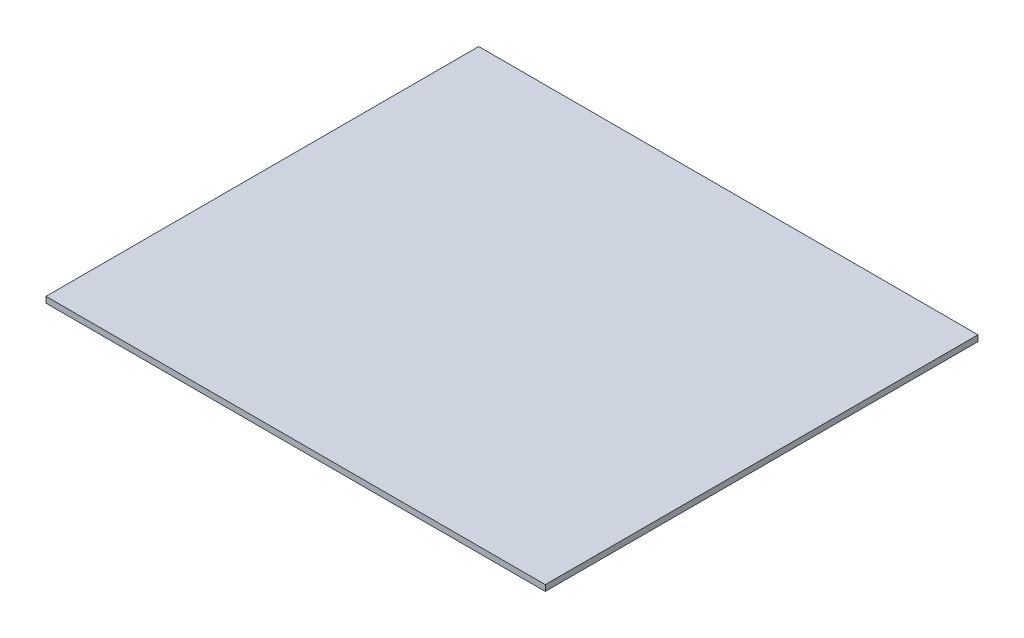
SolidWorks part; units mm, degrees
ref_plane "Front" through (0, 0, 0) normal (0, 0, 1) x (1, 0, 0)
ref_plane "Top" through (0, 0, 0) normal (0, 1, 0) x (1, 0, 0)
ref_plane "Right" through (0, 0, 0) normal (1, 0, 0) x (0, 0, -1)
sketch "草图1" plane through (0, 0, 0) normal (0, 0, 1) x (1, 0, 0)
  line L0 (-100, 20.5) -> (-105, 20.5)
  line L1 (-100, -20.5) -> (100, -20.5)
  line L2 (-100, -20.5) -> (-100, 20.5)
  line L3 (-100, 20.5) -> (100, 20.5)
  line L4 (100, -20.5) -> (100, 20.5)
  line L5 (-100, -20.5) -> (100, 20.5) construction
  line L6 (-100, 20.5) -> (100, -20.5) construction
  line L7 (-105, -23) -> (105, -23)
  line L8 (-105, -23) -> (-105, 23)
  line L9 (-105, 23) -> (105, 23)
  line L10 (105, -23) -> (105, 23)
  line L11 (-105, -23) -> (105, 23) construction
  line L12 (-105, 23) -> (105, -23) construction
  line L13 (-105, 20.5) -> (100, 20.5)
  line L14 (105, 20.5) -> (100, 20.5)
  point P0 (0, 0)
  point P6 (0, 0)
  dimension "D1" = 210
  dimension "D2" = 200
  dimension "D3" = 41
  dimension "D4" = 46
extrude "凸台-拉伸1" add sketch "草图1" along normal blind 182 contours L14 L10 L9 L8 L0 L3
